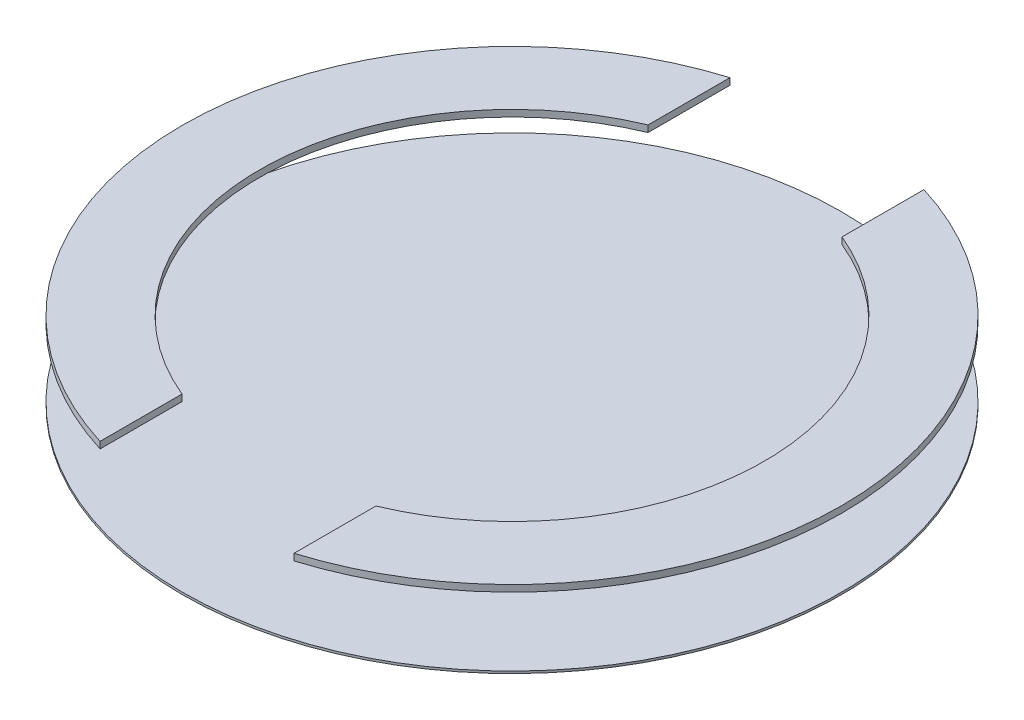
SolidWorks part; units mm, degrees
ref_plane "Front Plane" through (0, 0, 0) normal (0, 0, 1) x (1, 0, 0)
ref_plane "Top Plane" through (0, 0, 0) normal (0, 1, 0) x (1, 0, 0)
ref_plane "Right Plane" through (0, 0, 0) normal (1, 0, 0) x (0, 0, -1)
sketch "Sketch1" plane through (0, 0, 0) normal (0, 1, 0) x (1, 0, 0)
  line L0 (0, 1495.54) -> (0, -1495.54) construction
  line L1 (0, 0) -> (1057.5065, 1057.5065) construction
  line L2 (1057.5065, 1057.5065) -> (-1057.5065, -1057.5065) construction
  line L3 (-1057.5065, -1057.5065) -> (1057.5065, -1057.5065) construction
  line L4 (1057.5065, -1057.5065) -> (-1057.5065, 1057.5065) construction
  line L5 (-1057.5065, 1057.5065) -> (1057.5065, 1057.5065) construction
  line L6 (440.104, -1057.5065) -> (440.104, -1429.3174)
  line L7 (440.104, 1057.5065) -> (440.104, 1429.3174)
  line L8 (-440.104, 1057.5065) -> (-440.104, 1429.3174)
  line L9 (-440.104, -1057.5065) -> (-440.104, -1429.3174)
  circle A0 centre (0, 0) radius 1495.54
  arc A2 (440.104, 1057.5065) -> (440.104, -1057.5065) centre (0, 0) cw
  arc A3 (-440.104, 1057.5065) -> (-440.104, -1057.5065) centre (0, 0) ccw
extrude "Boss-Extrude4" add sketch "Sketch1" along normal blind 650 contours L7 A2 L6 A0 | A3 L8 A0 L9
sketch "Sketch3" plane through (0, 0, 0) normal (0, -1, 0) x (1, 0, 0)
  circle A0 centre (0, 0) radius 1495.54
extrude "Boss-Extrude5" add sketch "Sketch3" along normal blind 10
sketch "Sketch4" plane through (0, 0, 0) normal (0, 0, 1) x (1, 0, 0)
  line L0 (0, 0) -> (0, 325) construction
  line L1 (0, 325) -> (-1495.54, 325) construction
  line L2 (-1495.54, 650) -> (-1495.54, -10) construction
  line L3 (-1495.54, 325) -> (1495.54, 320) construction
  line L4 (1495.54, -10) -> (1495.54, 650) construction
  line L5 (0, 325) -> (0, 340) construction
  line L6 (0, 340) -> (0, 285.7716) construction
  line L7 (0, 285.7716) -> (1495.54, 285.7716) construction
  line L8 (1495.54, 285.7716) -> (-1495.54, 285.7716) construction
  line L9 (-1495.54, 285.7716) -> (-1495.54, 340) construction
  line L10 (-1495.54, 340) -> (1510.0343, 340) construction
  line L11 (1510.0343, 340) -> (1510.0343, 650)
  line L12 (1510.0343, 650) -> (-1495.54, 650)
  line L13 (-1495.54, 650) -> (-1495.54, 340)
  line L14 (-1495.54, 340) -> (1510.0343, 340)
extrude "Cut-Extrude1" cut sketch "Sketch4" against normal through all both and the other way through all contours L14 L11 L12 L13
sketch "Sketch5" plane through (0, 0, 0) normal (0, 0, 1) x (1, 0, 0)
  line L0 (0, 0) -> (0, 325) construction
  line L1 (0, 325) -> (0, 310) construction
  line L2 (0, 310) -> (-1495.54, 310) construction
  line L3 (-1495.54, 340) -> (-1495.54, -10) construction
  line L4 (-1495.54, 310) -> (1495.54, 310) construction
  line L5 (1495.54, -10) -> (1495.54, 340) construction
  line L6 (1495.54, 310) -> (1495.54, 0)
  line L7 (1495.54, 0) -> (-1495.54, 0)
  line L8 (-1495.54, 0) -> (-1495.54, 310)
  line L9 (-1495.54, 310) -> (1495.54, 310)
extrude "Cut-Extrude2" cut sketch "Sketch5" against normal through all both and the other way through all contours L9 L6 L7 L8
